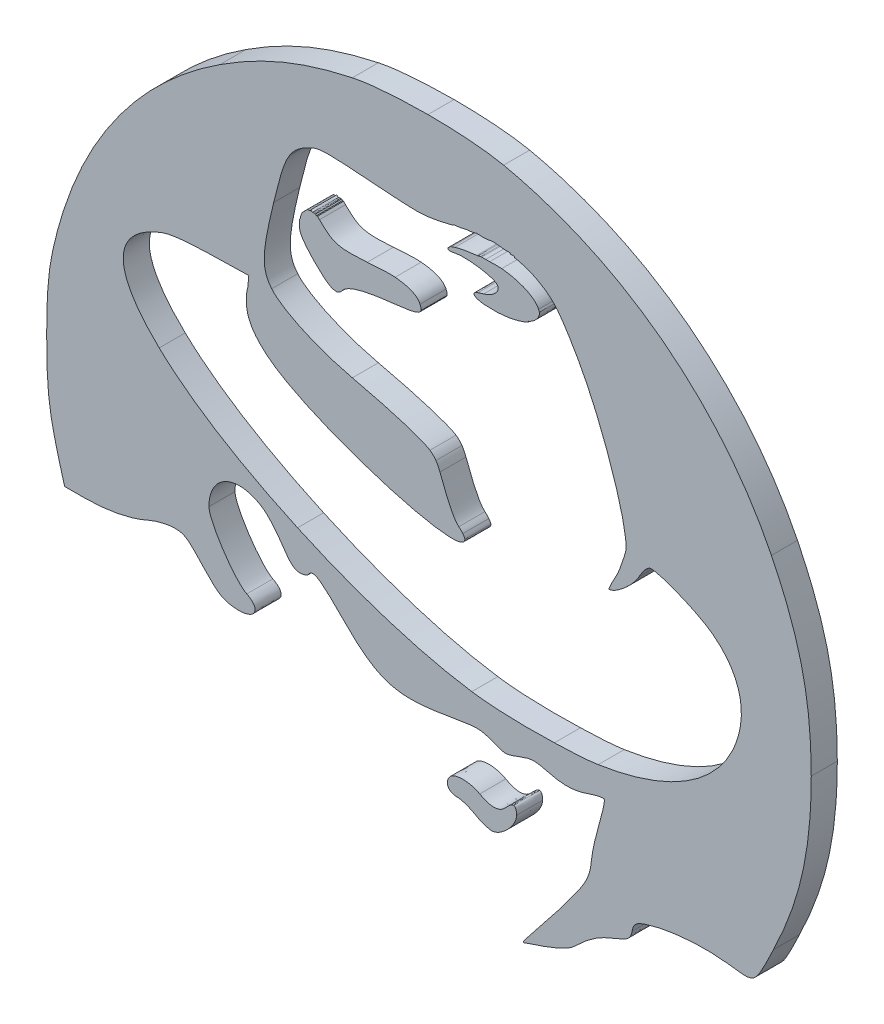
SolidWorks part; units mm, degrees
ref_plane "Alzado" through (0, 0, 0) normal (0, 0, 1) x (1, 0, 0)
ref_plane "Planta" through (0, 0, 0) normal (0, 1, 0) x (1, 0, 0)
ref_plane "Vista lateral" through (0, 0, 0) normal (1, 0, 0) x (0, 0, -1)
sketch "Model" plane through (0, 0, 0) normal (0, 0, 1) x (1, 0, 0)
  line L0 (1068.5563, 411.9054) -> (1068.7474, 411.2175)
  line L1 (1068.7474, 411.2175) -> (1069.5117, 411.2175)
  line L2 (1074.2505, 421.7269) -> (1075.8174, 421.7651)
  line L3 (1075.8174, 421.7651) -> (1075.7791, 421.3447)
  line L4 (1075.7791, 421.3447) -> (1075.7409, 421.1919)
  line L5 (1078.1103, 425.0899) -> (1078.0721, 425.0899)
  spline S0 degree 3 poles (1082.6962, 430.5548) (1081.5857, 430.5517) (1080.4803, 430.4735) (1079.7918, 430.3255) knots 0 0 0 0 1 1 1 1
  spline S1 degree 3 poles (1079.7918, 430.3255) (1077.8645, 429.9109) (1076.3527, 429.29) (1074.7091, 428.2236) knots 0 0 0 0 1 1 1 1
  spline S2 degree 3 poles (1074.7091, 428.2236) (1071.3571, 426.0481) (1069.1571, 422.8165) (1068.2888, 418.8225) knots 0 0 0 0 1 1 1 1
  spline S3 degree 3 poles (1068.2888, 418.8225) (1068.1286, 418.0826) (1068.0595, 417.3525) (1068.0595, 415.9181) knots 0 0 0 0 1 1 1 1
  spline S4 degree 3 poles (1068.0595, 415.9181) (1068.0595, 414.0421) (1068.1417, 413.4316) (1068.5563, 411.9054) knots 0 0 0 0 1 1 1 1
  spline S5 degree 3 poles (1069.5117, 411.2175) (1070.4375, 411.2175) (1071.3195, 411.4061) (1071.9958, 411.7143) knots 0 0 0 0 1 1 1 1
  spline S6 degree 3 poles (1071.9958, 411.7143) (1072.2587, 411.8341) (1072.698, 411.9424) (1072.9512, 411.9436) knots 0 0 0 0 1 1 1 1
  spline S7 degree 3 poles (1072.9512, 411.9436) (1073.3657, 411.946) (1073.4688, 411.8559) (1074.0594, 411.2175) knots 0 0 0 0 1 1 1 1
  spline S8 degree 3 poles (1074.0594, 411.2175) (1074.611, 410.6219) (1074.795, 410.5082) (1075.2059, 410.4532) knots 0 0 0 0 1 1 1 1
  spline S9 degree 3 poles (1075.2059, 410.4532) (1075.9996, 410.3456) (1076.3732, 410.8133) (1075.7409, 411.1411) knots 0 0 0 0 1 1 1 1
  spline S10 degree 3 poles (1075.7409, 411.1411) (1075.2628, 411.3881) (1074.2887, 412.8461) (1074.2887, 413.3194) knots 0 0 0 0 1 1 1 1
  spline S11 degree 3 poles (1074.2887, 413.3194) (1074.2887, 414.4714) (1075.4062, 414.9755) (1076.3906, 414.2748) knots 0 0 0 0 1 1 1 1
  spline S12 degree 3 poles (1076.3906, 414.2748) (1076.5704, 414.1476) (1076.91, 413.7556) (1077.1167, 413.434) knots 0 0 0 0 1 1 1 1
  spline S13 degree 3 poles (1077.1167, 413.434) (1077.3919, 413.0048) (1077.5658, 412.8608) (1077.7664, 412.8608) knots 0 0 0 0 1 1 1 1
  spline S14 degree 3 poles (1077.7664, 412.8608) (1077.9156, 412.8608) (1078.07, 412.9106) (1078.1103, 412.9754) knots 0 0 0 0 1 1 1 1
  spline S15 degree 3 poles (1078.1103, 412.9754) (1078.2717, 413.2384) (1078.561, 413.0412) (1079.4097, 412.1729) knots 0 0 0 0 1 1 1 1
  spline S16 degree 3 poles (1079.4097, 412.1729) (1080.7781, 410.7714) (1081.448, 410.5892) (1083.4988, 410.95) knots 0 0 0 0 1 1 1 1
  spline S17 degree 3 poles (1083.4988, 410.95) (1084.5957, 411.1444) (1084.7205, 411.1346) (1085.1803, 410.95) knots 0 0 0 0 1 1 1 1
  spline S18 degree 3 poles (1085.1803, 410.95) (1085.6401, 410.7665) (1085.6811, 410.7617) (1086.1739, 410.95) knots 0 0 0 0 1 1 1 1
  spline S19 degree 3 poles (1086.1739, 410.95) (1086.6166, 411.1187) (1086.7716, 411.1426) (1087.2057, 411.0264) knots 0 0 0 0 1 1 1 1
  spline S20 degree 3 poles (1087.2057, 411.0264) (1087.8881, 410.843) (1088.2856, 410.8531) (1088.8872, 411.0646) knots 0 0 0 0 1 1 1 1
  spline S21 degree 3 poles (1088.8872, 411.0646) (1089.1612, 411.16) (1089.4275, 411.2135) (1089.4605, 411.1793) knots 0 0 0 0 1 1 1 1
  spline S22 degree 3 poles (1089.4605, 411.1793) (1089.4935, 411.1463) (1089.4076, 410.7268) (1089.2694, 410.2621) knots 0 0 0 0 1 1 1 1
  spline S23 degree 3 poles (1089.2694, 410.2621) (1089.1312, 409.7974) (1088.9918, 409.1612) (1088.9637, 408.8481) knots 0 0 0 0 1 1 1 1
  spline S24 degree 3 poles (1088.9637, 408.8481) (1088.927, 408.4176) (1088.8078, 408.1299) (1088.4287, 407.587) knots 0 0 0 0 1 1 1 1
  spline S25 degree 3 poles (1088.4287, 407.587) (1087.3684, 406.0681) (1086.1024, 404.7269) (1086.4032, 404.8736) knots 0 0 0 0 1 1 1 1
  spline S26 degree 3 poles (1086.4032, 404.8736) (1086.5316, 404.9372) (1087.8958, 405.3047) (1088.314, 405.7144) knots 0 0 0 0 1 1 1 1
  spline S27 degree 3 poles (1088.314, 405.7144) (1088.8619, 406.25) (1089.2624, 406.5123) (1089.7662, 406.708) knots 0 0 0 0 1 1 1 1
  spline S28 degree 3 poles (1089.7662, 406.708) (1090.363, 406.9391) (1090.4804, 407.026) (1090.5305, 407.3195) knots 0 0 0 0 1 1 1 1
  spline S29 degree 3 poles (1090.5305, 407.3195) (1090.5782, 407.5958) (1090.6913, 407.694) (1091.0656, 407.8163) knots 0 0 0 0 1 1 1 1
  spline S30 degree 3 poles (1091.0656, 407.8163) (1091.9057, 408.0914) (1093.2002, 408.2085) (1094.1993, 408.0838) knots 0 0 0 0 1 1 1 1
  spline S31 degree 3 poles (1094.1993, 408.0838) (1095.3023, 407.9444) (1095.2002, 407.8597) (1095.9572, 409.4213) knots 0 0 0 0 1 1 1 1
  spline S32 degree 3 poles (1095.9572, 409.4213) (1097.0016, 411.5737) (1097.4094, 413.4319) (1097.4094, 415.9181) knots 0 0 0 0 1 1 1 1
  spline S33 degree 3 poles (1097.4094, 415.9181) (1097.4094, 418.4629) (1096.9826, 420.257) (1095.8808, 422.4912) knots 0 0 0 0 1 1 1 1
  spline S34 degree 3 poles (1095.8808, 422.4912) (1093.9143, 426.4779) (1090.1609, 429.3423) (1085.6007, 430.3255) knots 0 0 0 0 1 1 1 1
  spline S35 degree 3 poles (1085.6007, 430.3255) (1084.9311, 430.4698) (1083.8068, 430.5579) (1082.6962, 430.5548) knots 0 0 0 0 1 1 1 1
  spline S36 degree 3 poles (1085.1803, 427.574) (1085.1937, 427.574) (1085.2433, 427.574) (1085.2567, 427.574) knots 0 0 0 0 1 1 1 1
  spline S37 degree 3 poles (1085.2567, 427.574) (1085.3876, 427.5727) (1085.5141, 427.5492) (1085.6389, 427.5357) knots 0 0 0 0 1 1 1 1
  spline S38 degree 3 poles (1085.6389, 427.5357) (1085.6951, 427.5284) (1085.7749, 427.5431) (1085.83, 427.5357) knots 0 0 0 0 1 1 1 1
  spline S39 degree 3 poles (1085.83, 427.5357) (1085.841, 427.5333) (1085.8559, 427.5) (1085.8682, 427.4975) knots 0 0 0 0 1 1 1 1
  spline S40 degree 3 poles (1085.8682, 427.4975) (1085.9232, 427.489) (1085.9672, 427.5085) (1086.021, 427.4975) knots 0 0 0 0 1 1 1 1
  spline S41 degree 3 poles (1086.021, 427.4975) (1086.0296, 427.4951) (1086.0125, 427.4618) (1086.021, 427.4593) knots 0 0 0 0 1 1 1 1
  spline S42 degree 3 poles (1086.021, 427.4593) (1086.0785, 427.4471) (1086.1559, 427.4358) (1086.2121, 427.4211) knots 0 0 0 0 1 1 1 1
  spline S43 degree 3 poles (1086.2121, 427.4211) (1086.453, 427.3538) (1086.6823, 427.2722) (1086.9, 427.1536) knots 0 0 0 0 1 1 1 1
  spline S44 degree 3 poles (1086.9, 427.1536) (1087.2216, 426.9799) (1087.4405, 426.8124) (1087.6643, 426.5421) knots 0 0 0 0 1 1 1 1
  spline S45 degree 3 poles (1087.6643, 426.5421) (1087.794, 426.3856) (1087.9172, 426.1899) (1088.0847, 425.9307) knots 0 0 0 0 1 1 1 1
  spline S46 degree 3 poles (1088.0847, 425.9307) (1088.4247, 425.4024) (1088.8185, 424.6582) (1089.1548, 423.867) knots 0 0 0 0 1 1 1 1
  spline S47 degree 3 poles (1089.1548, 423.867) (1089.7894, 422.375) (1090.3012, 420.7076) (1090.3012, 419.969) knots 0 0 0 0 1 1 1 1
  spline S48 degree 3 poles (1090.3012, 419.969) (1090.3012, 419.8198) (1090.234, 419.6293) (1090.1484, 419.3957) knots 0 0 0 0 1 1 1 1
  spline S49 degree 3 poles (1090.1484, 419.3957) (1090.0897, 419.2355) (1090.0417, 419.0567) (1089.9573, 418.8989) knots 0 0 0 0 1 1 1 1
  spline S50 degree 3 poles (1089.9573, 418.8989) (1089.7641, 418.5369) (1089.6075, 418.2492) (1089.6516, 418.2492) knots 0 0 0 0 1 1 1 1
  spline S51 degree 3 poles (1089.6516, 418.2492) (1089.8937, 418.2492) (1090.5694, 418.8124) (1090.798, 419.2429) knots 0 0 0 0 1 1 1 1
  spline S52 degree 3 poles (1090.798, 419.2429) (1090.9497, 419.5278) (1091.1429, 419.7397) (1091.2566, 419.7397) knots 0 0 0 0 1 1 1 1
  spline S53 degree 3 poles (1091.2566, 419.7397) (1091.6688, 419.7397) (1093.0757, 419.1618) (1093.626, 418.746) knots 0 0 0 0 1 1 1 1
  spline S54 degree 3 poles (1093.626, 418.746) (1094.6264, 417.9854) (1094.9434, 416.9233) (1094.5814, 415.7652) knots 0 0 0 0 1 1 1 1
  spline S55 degree 3 poles (1094.5814, 415.7652) (1094.5301, 415.5989) (1094.4711, 415.4408) (1094.3904, 415.2684) knots 0 0 0 0 1 1 1 1
  spline S56 degree 3 poles (1094.3904, 415.2684) (1093.6383, 413.6872) (1091.8311, 412.6061) (1089.2312, 412.2111) knots 0 0 0 0 1 1 1 1
  spline S57 degree 3 poles (1089.2312, 412.2111) (1088.7469, 412.1377) (1088.1611, 412.116) (1087.5497, 412.0965) knots 0 0 0 0 1 1 1 1
  spline S58 degree 3 poles (1087.5497, 412.0965) (1086.4686, 412.061) (1085.2962, 412.0766) (1084.3778, 412.2111) knots 0 0 0 0 1 1 1 1
  spline S59 degree 3 poles (1084.3778, 412.2111) (1082.2572, 412.5217) (1079.8741, 413.3151) (1077.6899, 414.313) knots 0 0 0 0 1 1 1 1
  spline S60 degree 3 poles (1077.6899, 414.313) (1075.5731, 415.2779) (1073.64, 416.4393) (1072.3779, 417.6378) knots 0 0 0 0 1 1 1 1
  spline S61 degree 3 poles (1072.3779, 417.6378) (1070.623, 419.3058) (1070.538, 420.6064) (1072.1486, 421.383) knots 0 0 0 0 1 1 1 1
  spline S62 degree 3 poles (1072.1486, 421.383) (1072.617, 421.6092) (1072.9469, 421.6841) (1074.2505, 421.7269) knots 0 0 0 0 1 1 1 1
  spline S63 degree 3 poles (1075.7409, 421.1919) (1075.7091, 420.9204) (1075.7192, 420.6773) (1075.7791, 420.4658) knots 0 0 0 0 1 1 1 1
  spline S64 degree 3 poles (1075.7791, 420.4658) (1075.877, 420.1234) (1076.0907, 419.8268) (1076.5052, 419.4722) knots 0 0 0 0 1 1 1 1
  spline S65 degree 3 poles (1076.5052, 419.4722) (1078.0583, 418.1428) (1084.1102, 416.2947) (1084.1102, 417.141) knots 0 0 0 0 1 1 1 1
  spline S66 degree 3 poles (1084.1102, 417.141) (1084.1102, 417.185) (1084.0827, 417.2229) (1084.0338, 417.2938) knots 0 0 0 0 1 1 1 1
  spline S67 degree 3 poles (1084.0338, 417.2938) (1083.9971, 417.3452) (1083.9323, 417.4002) (1083.8809, 417.4467) knots 0 0 0 0 1 1 1 1
  spline S68 degree 3 poles (1083.8809, 417.4467) (1083.6767, 417.6301) (1083.4887, 418.005) (1083.1548, 418.8989) knots 0 0 0 0 1 1 1 1
  spline S69 degree 3 poles (1083.1548, 418.8989) (1083.1182, 418.998) (1083.0729, 419.108) (1083.002, 419.2046) knots 0 0 0 0 1 1 1 1
  spline S70 degree 3 poles (1083.002, 419.2046) (1082.9274, 419.3074) (1082.8473, 419.385) (1082.7727, 419.4339) knots 0 0 0 0 1 1 1 1
  spline S71 degree 3 poles (1082.7727, 419.4339) (1082.4718, 419.6321) (1081.3865, 419.9842) (1079.7918, 420.3511) knots 0 0 0 0 1 1 1 1
  spline S72 degree 3 poles (1079.7918, 420.3511) (1078.4601, 420.6569) (1077.1109, 421.2711) (1076.6963, 421.7651) knots 0 0 0 0 1 1 1 1
  spline S73 degree 3 poles (1076.6963, 421.7651) (1076.2903, 422.2482) (1076.324, 422.8144) (1076.7728, 424.6695) knots 0 0 0 0 1 1 1 1
  spline S74 degree 3 poles (1076.7728, 424.6695) (1077.0112, 425.6576) (1077.1543, 426.1863) (1077.3842, 426.5421) knots 0 0 0 0 1 1 1 1
  spline S75 degree 3 poles (1077.3842, 426.5421) (1077.5542, 426.8063) (1077.7502, 426.9711) (1078.0339, 427.1154) knots 0 0 0 0 1 1 1 1
  spline S76 degree 3 poles (1078.0339, 427.1154) (1078.5585, 427.3832) (1078.4466, 427.3835) (1081.6262, 427.1536) knots 0 0 0 0 1 1 1 1
  spline S77 degree 3 poles (1081.6262, 427.1536) (1082.4052, 427.0973) (1082.7916, 427.1343) (1083.6134, 427.3447) knots 0 0 0 0 1 1 1 1
  spline S78 degree 3 poles (1083.6134, 427.3447) (1083.6464, 427.352) (1083.6581, 427.3743) (1083.6899, 427.3829) knots 0 0 0 0 1 1 1 1
  spline S79 degree 3 poles (1083.6899, 427.3829) (1083.7755, 427.4049) (1083.873, 427.4027) (1083.9574, 427.4211) knots 0 0 0 0 1 1 1 1
  spline S80 degree 3 poles (1083.9574, 427.4211) (1084.0014, 427.4297) (1084.0674, 427.452) (1084.1102, 427.4593) knots 0 0 0 0 1 1 1 1
  spline S81 degree 3 poles (1084.1102, 427.4593) (1084.2179, 427.4801) (1084.3132, 427.4828) (1084.416, 427.4975) knots 0 0 0 0 1 1 1 1
  spline S82 degree 3 poles (1084.416, 427.4975) (1084.4527, 427.5024) (1084.4952, 427.5308) (1084.5306, 427.5357) knots 0 0 0 0 1 1 1 1
  spline S83 degree 3 poles (1084.5306, 427.5357) (1084.6358, 427.5492) (1084.7348, 427.5272) (1084.8363, 427.5357) knots 0 0 0 0 1 1 1 1
  spline S84 degree 3 poles (1084.8363, 427.5357) (1084.8669, 427.537) (1084.8834, 427.5345) (1084.9128, 427.5357) knots 0 0 0 0 1 1 1 1
  spline S85 degree 3 poles (1084.9128, 427.5357) (1085.0082, 427.5419) (1085.0886, 427.574) (1085.1803, 427.574) knots 0 0 0 0 1 1 1 1
  spline S86 degree 3 poles (1084.7217, 426.8478) (1084.674, 426.843) (1084.6547, 426.8157) (1084.607, 426.8096) knots 0 0 0 0 1 1 1 1
  spline S87 degree 3 poles (1084.607, 426.8096) (1084.6009, 426.8096) (1084.5749, 426.8109) (1084.5688, 426.8096) knots 0 0 0 0 1 1 1 1
  spline S88 degree 3 poles (1084.5688, 426.8096) (1084.2448, 426.7729) (1083.9421, 426.7265) (1083.7281, 426.6568) knots 0 0 0 0 1 1 1 1
  spline S89 degree 3 poles (1083.7281, 426.6568) (1083.6938, 426.6458) (1083.6428, 426.6296) (1083.6134, 426.6186) knots 0 0 0 0 1 1 1 1
  spline S90 degree 3 poles (1083.6134, 426.6186) (1083.5865, 426.6075) (1083.5578, 426.5913) (1083.537, 426.5803) knots 0 0 0 0 1 1 1 1
  spline S91 degree 3 poles (1083.537, 426.5803) (1083.515, 426.5693) (1083.5135, 426.5556) (1083.4988, 426.5421) knots 0 0 0 0 1 1 1 1
  spline S92 degree 3 poles (1083.4988, 426.5421) (1083.4817, 426.5299) (1083.4691, 426.5161) (1083.4606, 426.5039) knots 0 0 0 0 1 1 1 1
  spline S93 degree 3 poles (1083.4606, 426.5039) (1083.4545, 426.4935) (1083.462, 426.4736) (1083.4606, 426.4657) knots 0 0 0 0 1 1 1 1
  spline S94 degree 3 poles (1083.4606, 426.4657) (1083.485, 426.4363) (1083.5605, 426.429) (1083.7281, 426.4657) knots 0 0 0 0 1 1 1 1
  spline S95 degree 3 poles (1083.7281, 426.4657) (1084.1231, 426.5525) (1085.0345, 426.4373) (1085.2949, 426.2746) knots 0 0 0 0 1 1 1 1
  spline S96 degree 3 poles (1085.2949, 426.2746) (1085.5383, 426.1217) (1085.2888, 425.794) (1084.8363, 425.6632) knots 0 0 0 0 1 1 1 1
  spline S97 degree 3 poles (1084.8363, 425.6632) (1084.7569, 425.6411) (1084.6609, 425.6087) (1084.607, 425.5867) knots 0 0 0 0 1 1 1 1
  spline S98 degree 3 poles (1084.607, 425.5867) (1084.497, 425.539) (1084.4456, 425.5124) (1084.4542, 425.4721) knots 0 0 0 0 1 1 1 1
  spline S99 degree 3 poles (1084.4542, 425.4721) (1084.4676, 425.4134) (1084.6092, 425.34) (1084.8746, 425.3192) knots 0 0 0 0 1 1 1 1
  spline S100 degree 3 poles (1084.8746, 425.3192) (1085.5276, 425.2654) (1086.1623, 425.3788) (1086.5561, 425.5867) knots 0 0 0 0 1 1 1 1
  spline S101 degree 3 poles (1086.5561, 425.5867) (1086.5586, 425.5879) (1086.5549, 425.6237) (1086.5561, 425.6249) knots 0 0 0 0 1 1 1 1
  spline S102 degree 3 poles (1086.5561, 425.6249) (1086.5646, 425.6298) (1086.5869, 425.6188) (1086.5943, 425.6249) knots 0 0 0 0 1 1 1 1
  spline S103 degree 3 poles (1086.5943, 425.6249) (1086.8401, 425.7631) (1086.9899, 425.9395) (1086.9764, 426.1217) knots 0 0 0 0 1 1 1 1
  spline S104 degree 3 poles (1086.9764, 426.1217) (1086.9739, 426.1535) (1086.9505, 426.1664) (1086.9382, 426.1982) knots 0 0 0 0 1 1 1 1
  spline S105 degree 3 poles (1086.9382, 426.1982) (1086.8245, 426.5039) (1086.2555, 426.7806) (1085.5242, 426.8478) knots 0 0 0 0 1 1 1 1
  spline S106 degree 3 poles (1085.5242, 426.8478) (1085.3922, 426.8589) (1085.2234, 426.854) (1085.0656, 426.8478) knots 0 0 0 0 1 1 1 1
  spline S107 degree 3 poles (1085.0656, 426.8478) (1085.0155, 426.8466) (1084.9641, 426.8503) (1084.9128, 426.8478) knots 0 0 0 0 1 1 1 1
  spline S108 degree 3 poles (1084.9128, 426.8478) (1084.8663, 426.8442) (1084.8064, 426.8503) (1084.7599, 426.8478) knots 0 0 0 0 1 1 1 1
  spline S109 degree 3 poles (1084.7599, 426.8478) (1084.7526, 426.8466) (1084.729, 426.8491) (1084.7217, 426.8478) knots 0 0 0 0 1 1 1 1
  spline S110 degree 3 poles (1078.1868, 425.1281) (1078.1843, 425.1281) (1078.1892, 425.0899) (1078.1868, 425.0899) knots 0 0 0 0 1 1 1 1
  spline S111 degree 3 poles (1078.1868, 425.0899) (1078.1635, 425.0875) (1078.1323, 425.0973) (1078.1103, 425.0899) knots 0 0 0 0 1 1 1 1
  spline S112 degree 3 poles (1078.0721, 425.0899) (1078.0574, 425.0826) (1078.0498, 425.0603) (1078.0339, 425.0517) knots 0 0 0 0 1 1 1 1
  spline S113 degree 3 poles (1078.0339, 425.0517) (1078.0131, 425.037) (1077.977, 424.9948) (1077.9575, 424.9753) knots 0 0 0 0 1 1 1 1
  spline S114 degree 3 poles (1077.9575, 424.9753) (1077.9428, 424.9594) (1077.9302, 424.9542) (1077.9192, 424.937) knots 0 0 0 0 1 1 1 1
  spline S115 degree 3 poles (1077.9192, 424.937) (1077.9119, 424.9285) (1077.8871, 424.9074) (1077.881, 424.8988) knots 0 0 0 0 1 1 1 1
  spline S116 degree 3 poles (1077.881, 424.8988) (1077.8663, 424.8768) (1077.855, 424.8481) (1077.8428, 424.8224) knots 0 0 0 0 1 1 1 1
  spline S117 degree 3 poles (1077.8428, 424.8224) (1077.8281, 424.7894) (1077.8144, 424.7444) (1077.8046, 424.7078) knots 0 0 0 0 1 1 1 1
  spline S118 degree 3 poles (1077.8046, 424.7078) (1077.8021, 424.7016) (1077.8058, 424.6757) (1077.8046, 424.6695) knots 0 0 0 0 1 1 1 1
  spline S119 degree 3 poles (1077.8046, 424.6695) (1077.7948, 424.6341) (1077.7725, 424.6298) (1077.7664, 424.5931) knots 0 0 0 0 1 1 1 1
  spline S120 degree 3 poles (1077.7664, 424.5931) (1077.7664, 424.5858) (1077.7676, 424.5622) (1077.7664, 424.5549) knots 0 0 0 0 1 1 1 1
  spline S121 degree 3 poles (1077.7664, 424.5549) (1077.7627, 424.5109) (1077.7664, 424.4497) (1077.7664, 424.402) knots 0 0 0 0 1 1 1 1
  spline S122 degree 3 poles (1077.7664, 424.402) (1077.7664, 424.3189) (1077.7667, 424.262) (1077.8046, 424.1727) knots 0 0 0 0 1 1 1 1
  spline S123 degree 3 poles (1077.8046, 424.1727) (1077.8816, 423.9942) (1078.0608, 423.771) (1078.3396, 423.4848) knots 0 0 0 0 1 1 1 1
  spline S124 degree 3 poles (1078.3396, 423.4848) (1078.7407, 423.0776) (1078.9884, 422.8994) (1079.1804, 422.9116) knots 0 0 0 0 1 1 1 1
  spline S125 degree 3 poles (1079.1804, 422.9116) (1079.2745, 422.9177) (1079.3326, 422.9715) (1079.4097, 423.0645) knots 0 0 0 0 1 1 1 1
  spline S126 degree 3 poles (1079.4097, 423.0645) (1079.6127, 423.309) (1080.1694, 423.4772) (1081.2823, 423.5995) knots 0 0 0 0 1 1 1 1
  spline S127 degree 3 poles (1081.2823, 423.5995) (1082.0539, 423.6839) (1082.3713, 423.745) (1082.4287, 423.9052) knots 0 0 0 0 1 1 1 1
  spline S128 degree 3 poles (1082.4287, 423.9052) (1082.4471, 423.959) (1082.4199, 424.0205) (1082.3905, 424.0963) knots 0 0 0 0 1 1 1 1
  spline S129 degree 3 poles (1082.3905, 424.0963) (1082.3061, 424.3152) (1081.983, 424.4714) (1081.4351, 424.5167) knots 0 0 0 0 1 1 1 1
  spline S130 degree 3 poles (1081.4351, 424.5167) (1081.1392, 424.5411) (1080.787, 424.5066) (1080.3651, 424.4785) knots 0 0 0 0 1 1 1 1
  spline S131 degree 3 poles (1080.3651, 424.4785) (1079.2119, 424.4026) (1079.0468, 424.4714) (1078.5307, 424.9753) knots 0 0 0 0 1 1 1 1
  spline S132 degree 3 poles (1078.5307, 424.9753) (1078.5038, 425.0022) (1078.4812, 425.0334) (1078.4543, 425.0517) knots 0 0 0 0 1 1 1 1
  spline S133 degree 3 poles (1078.4543, 425.0517) (1078.4518, 425.0529) (1078.4185, 425.0517) (1078.416, 425.0517) knots 0 0 0 0 1 1 1 1
  spline S134 degree 3 poles (1078.416, 425.0517) (1078.394, 425.0676) (1078.4011, 425.0801) (1078.3778, 425.0899) knots 0 0 0 0 1 1 1 1
  spline S135 degree 3 poles (1078.3778, 425.0899) (1078.3717, 425.0924) (1078.3457, 425.0875) (1078.3396, 425.0899) knots 0 0 0 0 1 1 1 1
  spline S136 degree 3 poles (1078.3396, 425.0899) (1078.3188, 425.0985) (1078.3222, 425.085) (1078.3014, 425.0899) knots 0 0 0 0 1 1 1 1
  spline S137 degree 3 poles (1078.3014, 425.0899) (1078.2941, 425.0911) (1078.2693, 425.0887) (1078.2632, 425.0899) knots 0 0 0 0 1 1 1 1
  spline S138 degree 3 poles (1078.2632, 425.0899) (1078.2387, 425.0936) (1078.2112, 425.1306) (1078.1868, 425.1281) knots 0 0 0 0 1 1 1 1
  spline S139 degree 3 poles (1085.9828, 409.2303) (1085.9163, 409.2413) (1085.8196, 409.1581) (1085.6771, 409.001) knots 0 0 0 0 1 1 1 1
  spline S140 degree 3 poles (1085.6771, 409.001) (1085.4301, 408.7295) (1085.0932, 408.7292) (1084.6835, 408.9627) knots 0 0 0 0 1 1 1 1
  spline S141 degree 3 poles (1084.6835, 408.9627) (1084.3007, 409.1816) (1083.7192, 409.1804) (1083.537, 408.9627) knots 0 0 0 0 1 1 1 1
  spline S142 degree 3 poles (1083.537, 408.9627) (1083.3303, 408.7133) (1083.4621, 408.4277) (1083.8045, 408.4277) knots 0 0 0 0 1 1 1 1
  spline S143 degree 3 poles (1083.8045, 408.4277) (1083.9647, 408.4277) (1084.2821, 408.3268) (1084.4924, 408.1984) knots 0 0 0 0 1 1 1 1
  spline S144 degree 3 poles (1084.4924, 408.1984) (1084.7027, 408.07) (1084.9941, 407.9691) (1085.1421, 407.9691) knots 0 0 0 0 1 1 1 1
  spline S145 degree 3 poles (1085.1421, 407.9691) (1085.5089, 407.9679) (1086.0975, 408.5836) (1086.0975, 408.9627) knots 0 0 0 0 1 1 1 1
  spline S146 degree 3 poles (1086.0975, 408.9627) (1086.0975, 409.1431) (1086.0493, 409.2193) (1085.9828, 409.2303) knots 0 0 0 0 1 1 1 1
extrude "Boss-Extrude1" add sketch "Model" along normal blind 1 contours S145 S146 S139 S140 S141 S142 S143 S144 | S34 S35 S0 S1 S2 S3 S4 L0 L1 S5 S6 S7 S8 S9 S10 S11 S12 S13 S14 S15 S16 S17 S18 S19 S20 S21 S22 S23 S24 S25 S26 S27 S28 S29 S30 S31 S32 S33 S84 S85 S36 S37 S38 S39 S40 S41 S42 S43 S44 S45 | S137 S138 S110 S111 L5 S112 S113 S114 S115 S116 S117 S118 S119 S120 S121 S122 S123 S124 S125 S126 S127 S128 S129 S130 S131 S132 S133 S134 S135 S136 | S108 S109 S86 S87 S88 S89 S90 S91 S92 S93 S94 S95 S96 S97 S98 S99 S100 S101 S102 S103 S104 S105 S106 S107
